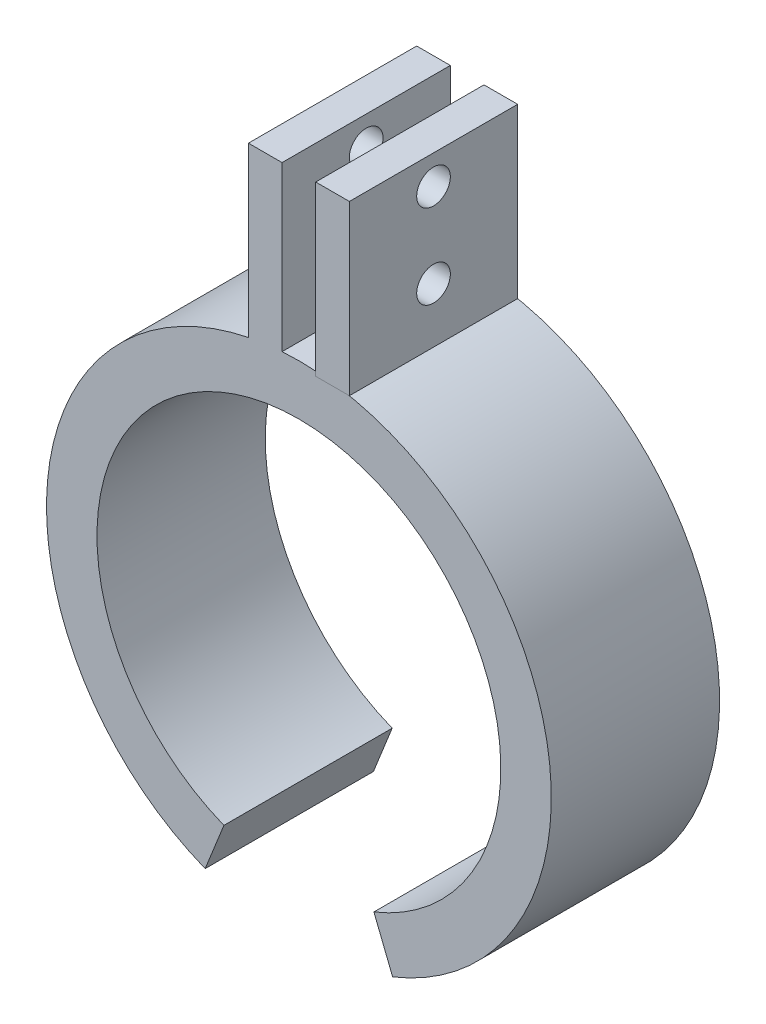
SolidWorks part; units mm, degrees
ref_plane "Front Plane" through (0, 0, 0) normal (0, 0, 1) x (1, 0, 0)
ref_plane "Top Plane" through (0, 0, 0) normal (0, 1, 0) x (1, 0, 0)
ref_plane "Right Plane" through (0, 0, 0) normal (1, 0, 0) x (0, 0, -1)
sketch "Sketch1" plane through (0, 0, 0) normal (0, 0, 1) x (1, 0, 0)
  arc A0 (4.4567, -11.1417) -> (-4.4567, -11.1417) centre (0, 0) ccw
extrude "Extrude-Thin1" add sketch "Sketch1" along normal blind 10 thin
sketch "Sketch3" plane through (0, 0, 10) normal (0, 0, 1) x (1, 0, 0)
  line L0 (-3, 14.6969) -> (-3, 24.6969)
  line L1 (4, 14.4568) -> (4, 23.1766)
  arc A0 (5.5709, -13.9272) -> (-5.5709, -13.9272) centre (0, 0) ccw construction
  dimension "D1" = 10
  dimension "D3" = 4
  dimension "D4" = 3
extrude "Extrude-Thin2" add sketch "Sketch3" against normal blind 10 thin contours L0
sketch "Sketch4" plane through (0, 0, 0) normal (0, 0, 1) x (1, 0, 0)
  line L1 (3, 14.6969) -> (3, 24.6969)
  arc A1 (5.5709, -13.9272) -> (-1, 14.9666) centre (0, 0) ccw construction
  dimension "D1" = 3
  dimension "D2" = 10
extrude "Extrude-Thin3" add sketch "Sketch4" along normal blind 10 separate body thin contours L1 thin type one direction reverse wall 2
sketch "Sketch5" plane through (-3, 0, 0) normal (-1, 0, 0) x (0, 0, 1)
  line L1 (10, 14.6969) -> (10, 24.6969) construction
  circle A0 centre (5, 22.9666) radius 1
  circle A1 centre (5, 17.9666) radius 1
  dimension "D3" = 5
  dimension "D1" = 3
  dimension "D2" = 5
  dimension "D4" = 5
extrude "Cut-Extrude1" cut sketch "Sketch5" against normal through all both and the other way through all
